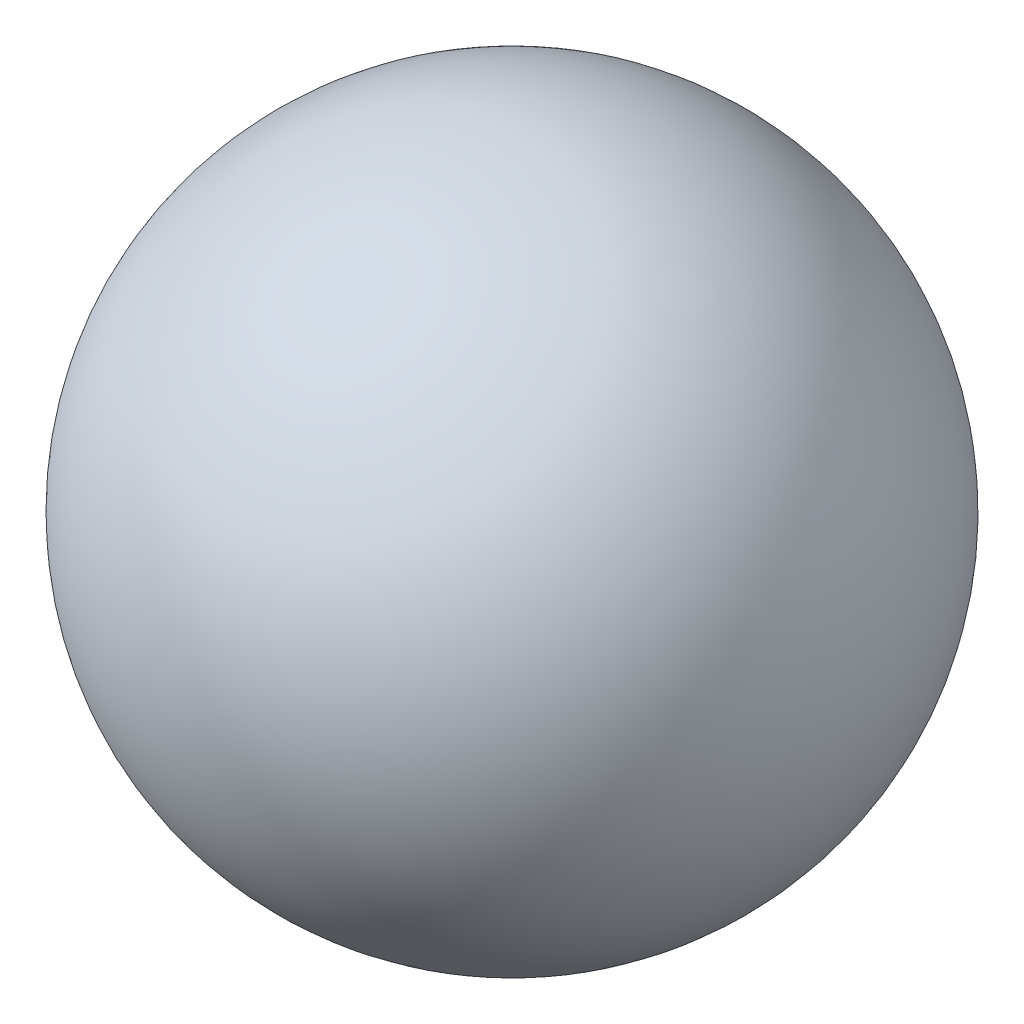
SolidWorks part; units mm, degrees
ref_plane "Front Plane" through (0, 0, 0) normal (0, 0, 1) x (1, 0, 0)
ref_plane "Top Plane" through (0, 0, 0) normal (0, 1, 0) x (1, 0, 0)
ref_plane "Right Plane" through (0, 0, 0) normal (1, 0, 0) x (0, 0, -1)
sketch "Sketch1" plane through (0, 0, 0) normal (0, 0, 1) x (1, 0, 0)
  line L0 (0, 49.0268) -> (0, -22.86) construction
  line L1 (0, 38.1) -> (0, 0)
  arc A0 (0, 38.1) -> (0, 0) centre (0, 19.05) cw
  dimension "D1" = 19.05
revolve "Revolve1" add sketch "Sketch1" angle 360 about L0
sketch "Sketch2" plane through (0, 0, 0) normal (0, 1, 0) x (1, 0, 0)
  circle A0 centre (0, 0) radius 6.35
  dimension "D1" = 12.7
extrude "Cut-Extrude1" cut sketch "Sketch2" along normal blind 19.05
cosmetic thread "Cosmetic Thread1" parameters "D1"=17.78, "D2"=14.2875
cosmetic thread "Cosmetic Thread2" parameters "D1"=17.78, "D2"=14.2875
